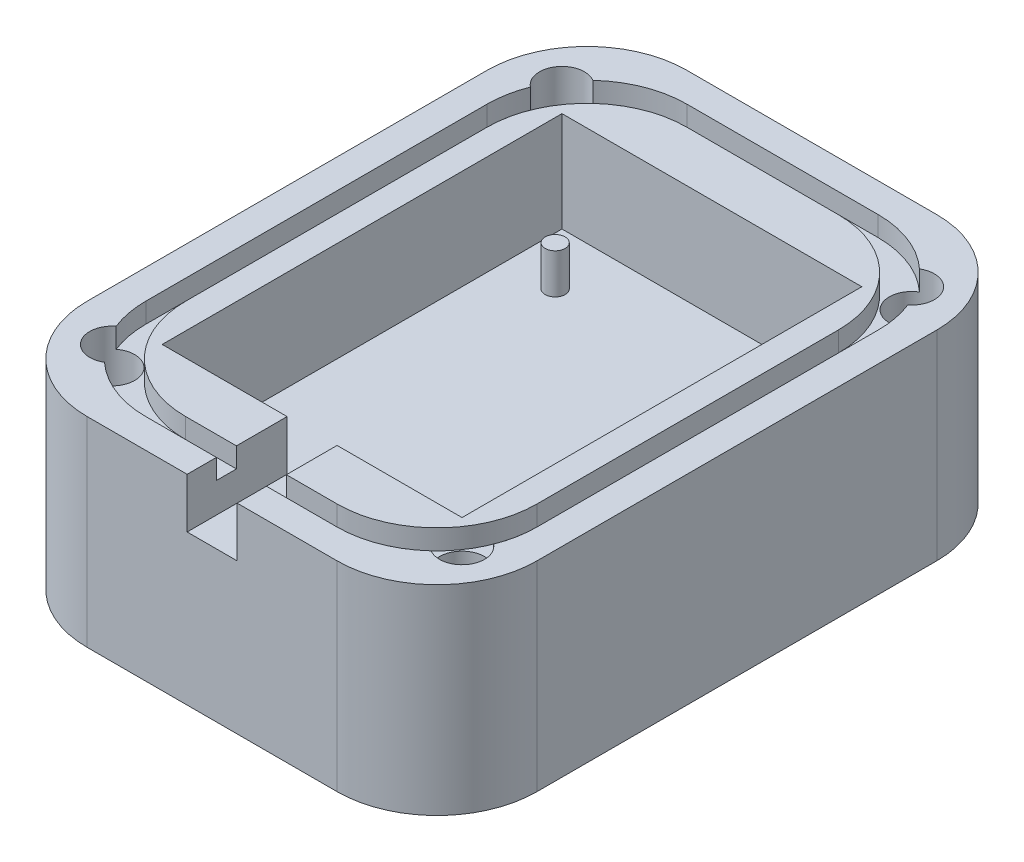
SolidWorks part; units mm, degrees
ref_plane "Plan de face" through (0, 0, 0) normal (0, 0, 1) x (1, 0, 0)
ref_plane "Plan de dessus" through (0, 0, 0) normal (0, 1, 0) x (1, 0, 0)
ref_plane "Plan de droite" through (0, 0, 0) normal (1, 0, 0) x (0, 0, -1)
sketch "Esquisse1" plane through (0, 0, 0) normal (0, 1, 0) x (1, 0, 0)
  line L1 (-12.5, 30) -> (12.5, 30)
  line L2 (-22.5, 20) -> (-22.5, -20)
  line L3 (-12.5, -30) -> (12.5, -30)
  line L4 (22.5, 20) -> (22.5, -20)
  arc A0 (-12.5, 30) -> (-22.5, 20) centre (-12.5, 20) ccw
  arc A1 (12.5, 30) -> (22.5, 20) centre (12.5, 20) cw
  arc A2 (12.5, -30) -> (22.5, -20) centre (12.5, -20) ccw
  arc A3 (-22.5, -20) -> (-12.5, -30) centre (-12.5, -20) ccw
  point P4 (0, 30)
  point P7 (-22.5, 0)
  point P10 (-22.5, 30)
  point P13 (22.5, 30)
  point P18 (-22.5, -30)
  dimension "D3" = 10
  dimension "D1" = 60
  dimension "D2" = 45
extrude "Boss.-Extru.1" add sketch "Esquisse1" along normal blind 10
sketch "Esquisse2" plane through (0, 10, 0) normal (0, 1, 0) x (1, 0, 0)
  line L1 (-15, 20) -> (15, 20)
  line L2 (-15, 20) -> (-15, -20)
  line L3 (-15, -20) -> (15, -20)
  line L4 (15, 20) -> (15, -20)
  point P4 (0, 20)
  point P6 (-15, 0)
  line M3 (-22.5, 20) -> (-22.5, -20)
  line M4 (-12.5, -30) -> (12.5, -30)
  line M5 (22.5, -20) -> (22.5, 20)
  line M6 (12.5, 30) -> (-12.5, 30)
  dimension "D1" = 30
  dimension "D2" = 40
extrude "Boss.-Extru.2" add sketch "Esquisse2" along normal blind 10 contours L1 L4 L3 L2 M6 M3 M4 M5
sketch "Esquisse3" plane through (0, 10, 0) normal (0, 1, 0) x (1, 0, 0)
  line L0 (-12.7, 17.018) -> (-12.7, -17.018) construction
  line L1 (-12.7, -17.018) -> (12.7, -17.018) construction
  line L2 (12.7, -17.018) -> (12.7, 17.018) construction
  line L3 (12.7, 17.018) -> (-12.7, 17.018) construction
  line L4 (-10.16, 14.478) -> (10.16, 14.478) construction
  circle A0 centre (-10.16, 14.478) radius 1
  circle A1 centre (10.16, 14.478) radius 1
  point P2 (-12.7, 0)
  point P5 (0, 17.018)
  point P11 (0, 14.478)
  dimension "D3" = 2
  dimension "D4" = 2
  dimension "D1" = 34.036
  dimension "D2" = 25.4
  dimension "D5" = 20.32
  dimension "D6" = 31.496
extrude "Boss.-Extru.3" add sketch "Esquisse3" along normal blind 4
sketch "Esquisse4" plane through (0, 20, 0) normal (0, 1, 0) x (1, 0, 0)
  line L0 (-12.5, -30) -> (12.5, -30) construction
  line L1 (-2.5, -30) -> (2.5, -30)
  line L2 (-2.5, -30) -> (-2.5, -20)
  line L3 (-2.5, -20) -> (2.5, -20)
  line L4 (2.5, -30) -> (2.5, -20)
  line L5 (-15, -20) -> (15, -20) construction
  point P8 (0, -20)
  dimension "D1" = 5
extrude "Enlèv. mat.-Extru.1" cut sketch "Esquisse4" against normal blind 5
sketch "Esquisse5" plane through (0, 20, 0) normal (0, 1, 0) x (1, 0, 0)
  line L0 (-17.5, 22.5) -> (17.5, 22.5) construction
  line L1 (-17.5, 22.5) -> (-17.5, -22.5) construction
  circle A0 centre (-17.5, -22.5) radius 2.25
  circle A1 centre (17.5, -22.5) radius 2.25
  circle A2 centre (17.5, 22.5) radius 2.25
  circle A3 centre (-17.5, 22.5) radius 2.25
  point P8 (-17.5, 0)
  point P9 (0, 22.5)
  dimension "D1" = 4.5
  dimension "D2" = 4.5
  dimension "D3" = 4.5
  dimension "D4" = 4.5
  dimension "D5" = 45
  dimension "D6" = 35
extrude "Enlèv. mat.-Extru.2" cut sketch "Esquisse5" against normal blind 10
sketch "Sketch1" plane through (0, 20, 0) normal (0, 1, 0) x (1, 0, 0)
  line L1 (-9.5711, 27.0711) -> (9.5711, 27.0711)
  line L2 (-19.5711, 17.0711) -> (-19.5711, -17.0711)
  line L3 (-9.5711, -27.0711) -> (9.5711, -27.0711)
  line L4 (19.5711, 17.0711) -> (19.5711, -17.0711)
  line L5 (-7.5711, 25.0711) -> (7.5711, 25.0711)
  line L6 (-17.5711, 15.0711) -> (-17.5711, -15.0711)
  line L7 (-7.5711, -25.0711) -> (7.5711, -25.0711)
  line L8 (17.5711, 15.0711) -> (17.5711, -15.0711)
  arc A0 (-12.5, 30) -> (-22.5, 20) centre (-12.5, 20) ccw construction
  arc A1 (12.5, -30) -> (22.5, -20) centre (12.5, -20) ccw construction
  arc A2 (-17.5711, -15.0711) -> (-7.5711, -25.0711) centre (-7.5711, -15.0711) ccw
  arc A3 (-19.5711, -17.0711) -> (-18.8803, -20.7231) centre (-9.5711, -17.0711) ccw
  arc A4 (9.5711, -27.0711) -> (16.3426, -24.4295) centre (9.5711, -17.0711) ccw
  arc A5 (7.5711, -25.0711) -> (17.5711, -15.0711) centre (7.5711, -15.0711) ccw
  arc A6 (9.5711, 27.0711) -> (16.3426, 24.4295) centre (9.5711, 17.0711) cw
  arc A7 (7.5711, 25.0711) -> (17.5711, 15.0711) centre (7.5711, 15.0711) cw
  arc A8 (-7.5711, 25.0711) -> (-17.5711, 15.0711) centre (-7.5711, 15.0711) ccw
  arc A9 (-9.5711, 27.0711) -> (-16.3426, 24.4295) centre (-9.5711, 17.0711) ccw
  circle A10 centre (17.5, 22.5) radius 2.25 construction
  arc A11 (16.3426, 24.4295) -> (18.8803, 20.7231) centre (17.5, 22.5) ccw
  circle A12 centre (17.5, -22.5) radius 2.25 construction
  circle A13 centre (-17.5, -22.5) radius 2.25 construction
  circle A14 centre (-17.5, 22.5) radius 2.25 construction
  arc A15 (18.8803, -20.7231) -> (16.3426, -24.4295) centre (17.5, -22.5) ccw
  arc A16 (-16.3426, -24.4295) -> (-18.8803, -20.7231) centre (-17.5, -22.5) ccw
  arc A17 (-18.8803, 20.7231) -> (-16.3426, 24.4295) centre (-17.5, 22.5) ccw
  arc A18 (18.8803, 20.7231) -> (19.5711, 17.0711) centre (9.5711, 17.0711) cw
  arc A19 (-18.8803, 20.7231) -> (-19.5711, 17.0711) centre (-9.5711, 17.0711) ccw
  arc A20 (-16.3426, -24.4295) -> (-9.5711, -27.0711) centre (-9.5711, -17.0711) ccw
  arc A21 (18.8803, -20.7231) -> (19.5711, -17.0711) centre (9.5711, -17.0711) ccw
  point P14 (-17.5711, 0)
  point P15 (-19.5711, 0)
  point P16 (0, 25.0711)
  point P17 (0, 27.0711)
  point P24 (19.5711, -27.0711)
  point P35 (-19.5711, 27.0711)
  dimension "D3" = 10
  dimension "D1" = 2
  dimension "D2" = 2
extrude "Cut-Extrude1" cut sketch "Sketch1" against normal blind 2
